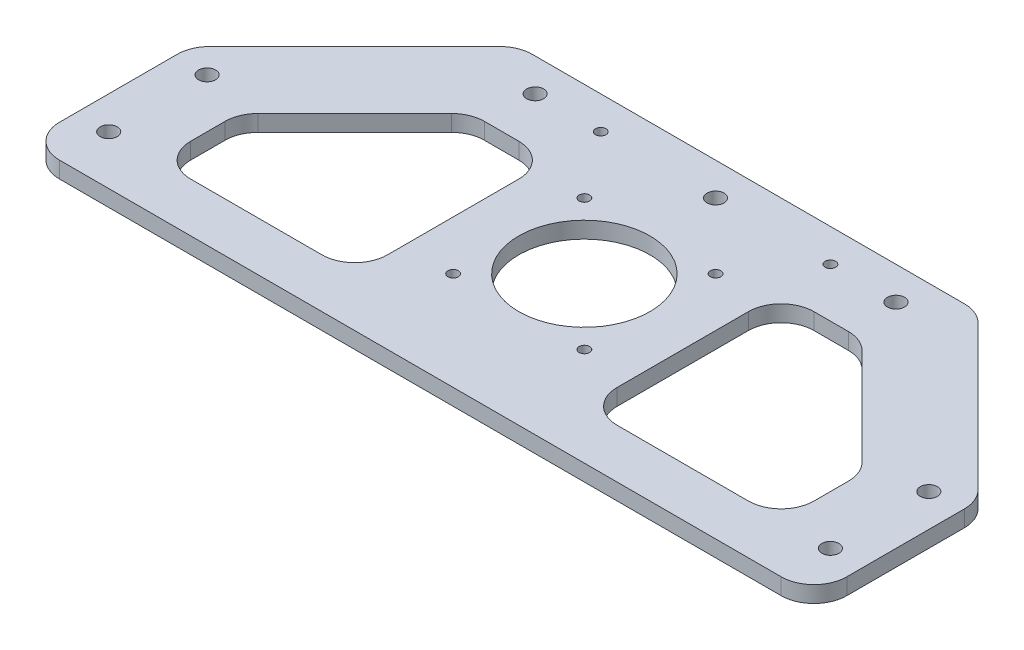
SolidWorks part; units mm, degrees
ref_plane "正面" through (0, 0, 0) normal (0, 0, 1) x (1, 0, 0)
ref_plane "平面" through (0, 0, 0) normal (0, 1, 0) x (1, 0, 0)
ref_plane "右側面" through (0, 0, 0) normal (1, 0, 0) x (0, 0, -1)
sketch "ｽｹｯﾁ1" plane through (0, 0, 0) normal (0, 1, 0) x (1, 0, 0)
  line L0 (-120, -50) -> (-120, 0)
  line L1 (-120, 0) -> (-70, 50)
  line L2 (-70, 50) -> (70, 50)
  line L3 (0, 50) -> (0, -50) construction
  line L4 (120, -50) -> (-120, -50)
  line L5 (-100, -50) -> (-100, 20) construction
  line L6 (-120, 0) -> (0, 0) construction
  line L7 (-110, -50) -> (-110, 10) construction
  line L8 (0, 40) -> (-80, 40) construction
  line L9 (120, -50) -> (120, 0)
  line L10 (120, 0) -> (70, 50)
  circle A0 centre (0, 0) radius 20
  circle A1 centre (-110, -35) radius 2.6
  circle A2 centre (-110, -5) radius 2.6
  circle A3 centre (-55, 40) radius 2.6
  circle A4 centre (0, 40) radius 2.6
  circle A5 centre (110, -35) radius 2.6
  circle A6 centre (110, -5) radius 2.6
  circle A7 centre (55, 40) radius 2.6
  dimension "D1" = 40
  dimension "D9" = 5.2
  dimension "D2" = 20
  dimension "D3" = 100
  dimension "D4" = 100
  dimension "D5" = 50
  dimension "D6" = 135
  dimension "D7" = 10
  dimension "D8" = 10
  dimension "D10" = 15
  dimension "D11" = 15
  dimension "D12" = 25
extrude "ﾎﾞｽ - 押し出し1" add sketch "ｽｹｯﾁ1" along normal blind 5
sketch "ｽｹｯﾁ2" plane through (0, 5, 0) normal (0, 1, 0) x (1, 0, 0)
  line L0 (-62.5736, 22.0711) -> (-92.0711, -7.4264)
  line L1 (-95, -14.4975) -> (-95, -25)
  line L2 (-85, -35) -> (-45, -35)
  line L3 (-35, -25) -> (-35, 15)
  line L4 (-45, 25) -> (-55.5025, 25)
  line L5 (0, 50) -> (0, -50) construction
  line L6 (70, 50) -> (-70, 50) construction
  line L7 (-120, -50) -> (120, -50) construction
  line L8 (-70, 50) -> (-120, 0) construction
  line L9 (-120, 0) -> (-120, -50) construction
  line L10 (35, -25) -> (35, 15)
  line L11 (85, -35) -> (45, -35)
  line L12 (95, -14.4975) -> (95, -25)
  line L13 (62.5736, 22.0711) -> (92.0711, -7.4264)
  line L14 (45, 25) -> (55.5025, 25)
  arc A0 (85, -35) -> (95, -25) centre (85, -25) ccw
  arc A1 (95, -14.4975) -> (92.0711, -7.4264) centre (85, -14.4975) ccw
  arc A2 (62.5736, 22.0711) -> (55.5025, 25) centre (55.5025, 15) ccw
  arc A3 (35, -25) -> (45, -35) centre (45, -25) ccw
  arc A4 (35, 15) -> (45, 25) centre (45, 15) cw
  arc A5 (-45, -35) -> (-35, -25) centre (-45, -25) ccw
  arc A6 (-35, 15) -> (-45, 25) centre (-45, 15) ccw
  arc A7 (-62.5736, 22.0711) -> (-55.5025, 25) centre (-55.5025, 15) cw
  arc A8 (-92.0711, -7.4264) -> (-95, -14.4975) centre (-85, -14.4975) ccw
  arc A9 (-95, -25) -> (-85, -35) centre (-85, -25) ccw
  point P22 (95, -35)
  point P25 (95, -10.3553)
  point P28 (59.6447, 25)
  point P31 (35, -35)
  point P34 (35, 25)
  point P37 (-35, -35)
  point P40 (-35, 25)
  point P43 (-59.6447, 25)
  point P46 (-95, -10.3553)
  point P49 (-95, -35)
  dimension "D6" = 10
  dimension "D1" = 25
  dimension "D2" = 25
  dimension "D3" = 25
  dimension "D4" = 15
  dimension "D5" = 35
extrude "ｶｯﾄ - 押し出し2" cut sketch "ｽｹｯﾁ2" against normal blind 5
fillet "ﾌｨﾚｯﾄ1" radius 10 6 edges at (70, 2.5, -50) (120, 2.5, 0) (120, 2.5, 50) (-120, 2.5, 50) (-120, 2.5, 0) (-70, 2.5, -50)
sketch "ｽｹｯﾁ3" plane through (0, 5, 0) normal (0, 1, 0) x (1, 0, 0)
  line L1 (-20, 20) -> (20, 20) construction
  line L2 (-20, 20) -> (-20, -20) construction
  line L3 (-20, -20) -> (20, -20) construction
  line L4 (20, 20) -> (20, -20) construction
  line L5 (-20, 20) -> (20, -20) construction
  line L6 (-20, -20) -> (20, 20) construction
  circle A0 centre (-20, 20) radius 1.6
  circle A1 centre (20, 20) radius 1.6
  circle A2 centre (20, -20) radius 1.6
  circle A3 centre (-20, -20) radius 1.6
  point P0 (0, 0)
  point P1 (22.5, -22.5)
  point P6 (0, 0)
  dimension "D2" = 4
  dimension "D3" = 3.2
  dimension "D1" = 40
extrude "ｶｯﾄ - 押し出し3" cut sketch "ｽｹｯﾁ3" against normal through all
sketch "ｽｹｯﾁ4" plane through (0, 5, 0) normal (0, 1, 0) x (1, 0, 0)
  line L0 (0, 40) -> (0, 0) construction
  line L1 (0, 40) -> (-35, 40) construction
  circle A0 centre (-35, 40) radius 1.6
  circle A1 centre (35, 40) radius 1.6
  dimension "D1" = 35
  dimension "D2" = 3.2
extrude "ｶｯﾄ - 押し出し4" cut sketch "ｽｹｯﾁ4" against normal through all
